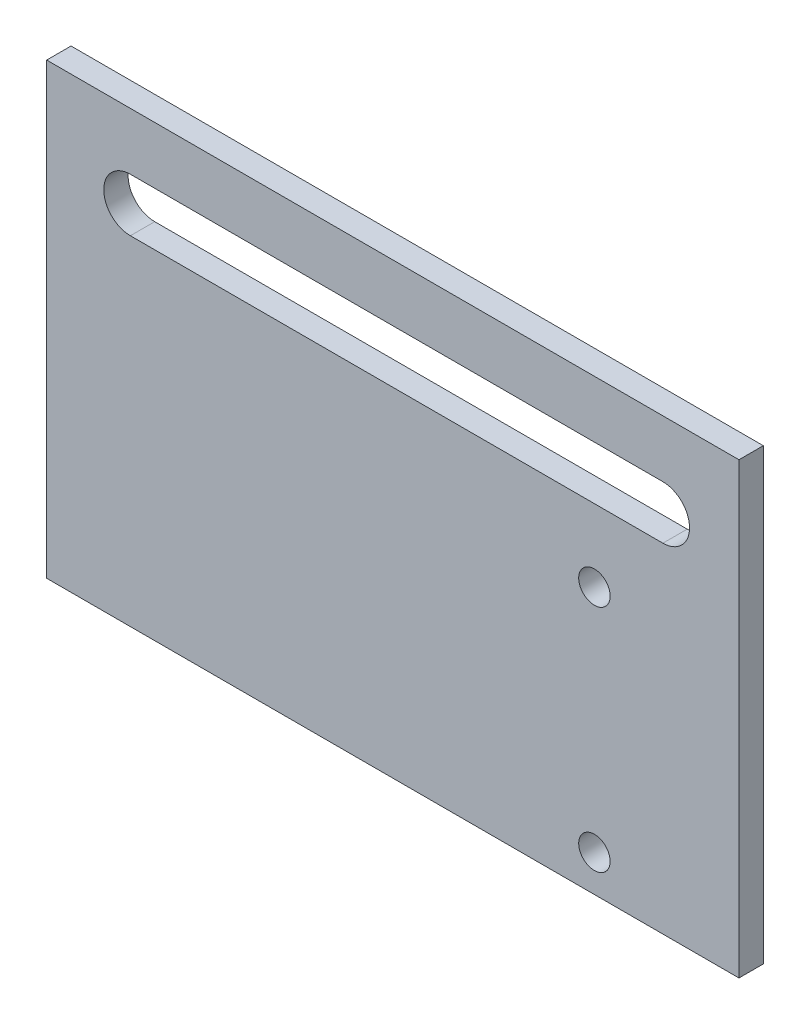
SolidWorks part; units mm, degrees
ref_plane "正面" through (0, 0, 0) normal (0, 0, 1) x (1, 0, 0)
ref_plane "平面" through (0, 0, 0) normal (0, 1, 0) x (1, 0, 0)
ref_plane "右側面" through (0, 0, 0) normal (1, 0, 0) x (0, 0, -1)
sketch "ｽｹｯﾁ1" plane through (0, 0, 0) normal (0, 0, 1) x (1, 0, 0)
  line L1 (0, 0) -> (91, 0)
  line L2 (0, 0) -> (0, 59)
  line L3 (0, 59) -> (91, 59)
  line L4 (91, 0) -> (91, 59)
extrude "ﾎﾞｽ - 押し出し1" add sketch "ｽｹｯﾁ1" along normal blind 3.2
sketch "ｽｹｯﾁ2" plane through (0, 0, 0) normal (0, 0, 1) x (1, 0, 0)
  line L0 (11, 48) -> (81, 48) construction
  line L1 (11, 51.5) -> (81, 51.5)
  line L2 (11, 44.5) -> (81, 44.5)
  arc A0 (11, 51.5) -> (11, 44.5) centre (11, 48) ccw
  arc A1 (81, 44.5) -> (81, 51.5) centre (81, 48) ccw
  point P2 (46, 48)
  point P7 (0, 0)
extrude "ｶｯﾄ - 押し出し1" cut sketch "ｽｹｯﾁ2" against normal through all and the other way through all
sketch "ｽｹｯﾁ3" plane through (0, 0, 0) normal (0, 0, 1) x (1, 0, 0)
  circle A0 centre (72, 35) radius 2.067
  circle A1 centre (72, 4.8) radius 2.067
extrude "ｶｯﾄ - 押し出し2" cut sketch "ｽｹｯﾁ3" against normal through all and the other way through all
